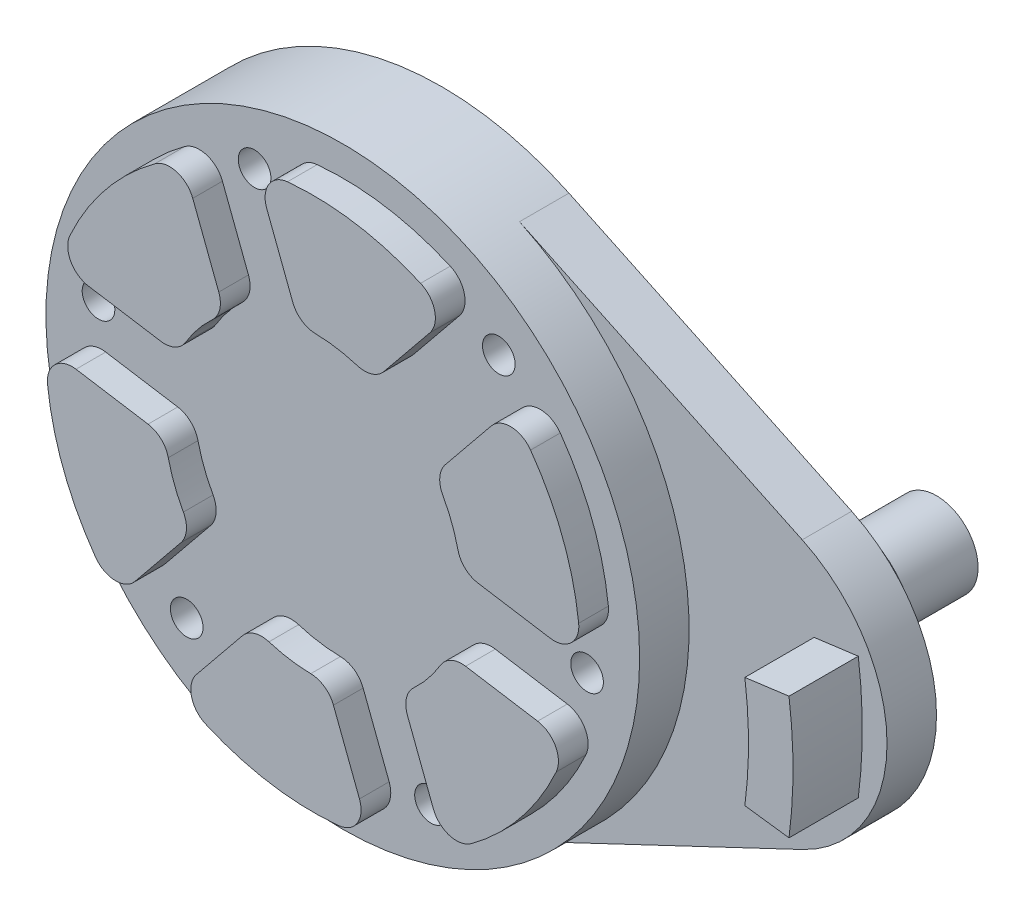
SolidWorks part; units mm, degrees
ref_plane "前视基准面" through (0, 0, 0) normal (0, 0, 1) x (1, 0, 0)
ref_plane "上视基准面" through (0, 0, 0) normal (0, 1, 0) x (1, 0, 0)
ref_plane "右视基准面" through (0, 0, 0) normal (1, 0, 0) x (0, 0, -1)
other "Configuration Table"
sketch "草图1" plane through (0, 0, 0) normal (0, 0, 1) x (1, 0, 0)
  line L0 (12.8571, 27.1052) -> (41.4286, 13.5526)
  line L1 (0, 0) -> (35, 0) construction
  line L2 (12.8571, -27.1052) -> (41.4286, -13.5526)
  arc A0 (12.8571, 27.1052) -> (12.8571, -27.1052) centre (0, 0) ccw
  arc A1 (41.4286, -13.5526) -> (41.4286, 13.5526) centre (35, 0) ccw
  dimension "D1" = 30
  dimension "D2" = 15
  dimension "D3" = 35
extrude "凸台-拉伸1" add sketch "草图1" along normal blind 10
sketch "草图2" plane through (0, 0, 10) normal (0, 0, 1) x (1, 0, 0)
  line L0 (23.9574, 0.2099) -> (16.6764, 1.3773) construction
  line L1 (13.353, 10.0845) -> (18.0045, 15.8063) construction
  line L2 (23.9574, 0.2099) -> (16.6764, 1.3773)
  line L3 (13.353, 10.0845) -> (18.0045, 15.8063)
  line L4 (15.4099, -6.5218) -> (22.6909, -7.6892)
  line L5 (12.1605, -20.6428) -> (9.531, -13.7536)
  line L6 (2.0569, -16.6063) -> (4.6864, -23.4955)
  line L7 (-11.7969, -20.8526) -> (-7.1455, -15.1308)
  line L8 (-13.353, -10.0845) -> (-18.0045, -15.8063)
  line L9 (-23.9574, -0.2099) -> (-16.6764, -1.3773)
  line L10 (-15.4099, 6.5218) -> (-22.6909, 7.6892)
  line L11 (-12.1605, 20.6428) -> (-9.531, 13.7536)
  line L12 (-2.0569, 16.6063) -> (-4.6864, 23.4955)
  line L13 (11.7969, 20.8526) -> (7.1455, 15.1308)
  arc A0 (21.9795, 15.6812) -> (18.0045, 15.8063) centre (19.9444, 14.2293) ccw construction
  arc A1 (26.8382, 2.9517) -> (21.9795, 15.6812) centre (0, 0) ccw construction
  arc A2 (26.8216, 2.2826) -> (26.8382, 2.9517) centre (24.3532, 2.6784) ccw construction
  arc A3 (23.9574, 0.2099) -> (26.8216, 2.2826) centre (24.3532, 2.6784) ccw construction
  arc A4 (14.6333, 3.2964) -> (16.6764, 1.3773) centre (17.0722, 3.8458) ccw construction
  arc A5 (14.6333, 3.2964) -> (13.1082, 7.2921) centre (0, 0) ccw construction
  arc A6 (12.8244, 8.9033) -> (13.1082, 7.2921) centre (15.2929, 8.5075) ccw construction
  arc A7 (13.353, 10.0845) -> (12.8244, 8.9033) centre (15.2929, 8.5075) ccw construction
  arc A8 (21.9795, 15.6812) -> (18.0045, 15.8063) centre (19.9444, 14.2293) ccw
  arc A9 (26.8382, 2.9517) -> (21.9795, 15.6812) centre (0, 0) ccw
  arc A10 (26.8216, 2.2826) -> (26.8382, 2.9517) centre (24.3532, 2.6784) ccw
  arc A11 (23.9574, 0.2099) -> (26.8216, 2.2826) centre (24.3532, 2.6784) ccw
  arc A12 (14.6333, 3.2964) -> (16.6764, 1.3773) centre (17.0722, 3.8458) ccw
  arc A13 (14.6333, 3.2964) -> (13.1082, 7.2921) centre (0, 0) ccw
  arc A14 (12.8244, 8.9033) -> (13.1082, 7.2921) centre (15.2929, 8.5075) ccw
  arc A15 (13.353, 10.0845) -> (12.8244, 8.9033) centre (15.2929, 8.5075) ccw
  arc A16 (24.5701, -11.1942) -> (22.6909, -7.6892) centre (22.2951, -10.1577) ccw
  arc A17 (15.4099, -6.5218) -> (14.1227, -6.6547) centre (15.0141, -8.9903) ccw
  arc A18 (14.1227, -6.6547) -> (12.8693, -7.706) centre (15.0141, -8.9903) ccw
  arc A19 (10.1714, -11.0246) -> (12.8693, -7.706) centre (0, 0) ccw
  arc A20 (10.1714, -11.0246) -> (9.531, -13.7536) centre (11.8666, -12.8621) ccw
  arc A21 (12.1605, -20.6428) -> (15.3876, -22.0869) centre (14.4961, -19.7513) ccw
  arc A22 (15.3876, -22.0869) -> (15.9753, -21.7667) centre (14.4961, -19.7513) ccw
  arc A23 (15.9753, -21.7667) -> (24.5701, -11.1942) centre (0, 0) ccw
  arc A24 (2.5906, -26.8754) -> (4.6864, -23.4955) centre (2.3507, -24.387) ccw
  arc A25 (2.0569, -16.6063) -> (1.2982, -15.5579) centre (-0.2788, -17.4978) ccw
  arc A26 (1.2982, -15.5579) -> (-0.2389, -14.9981) centre (-0.2788, -17.4978) ccw
  arc A27 (-4.4619, -14.321) -> (-0.2389, -14.9981) centre (0, 0) ccw
  arc A28 (-4.4619, -14.321) -> (-7.1455, -15.1308) centre (-5.2056, -16.7078) ccw
  arc A29 (-11.7969, -20.8526) -> (-11.434, -24.3695) centre (-9.8571, -22.4296) ccw
  arc A30 (-11.434, -24.3695) -> (-10.8629, -24.7184) centre (-9.8571, -22.4296) ccw
  arc A31 (-10.8629, -24.7184) -> (2.5906, -26.8754) centre (0, 0) ccw
  arc A32 (-21.9795, -15.6812) -> (-18.0045, -15.8063) centre (-19.9444, -14.2293) ccw
  arc A33 (-13.353, -10.0845) -> (-12.8244, -8.9033) centre (-15.2929, -8.5075) ccw
  arc A34 (-12.8244, -8.9033) -> (-13.1082, -7.2921) centre (-15.2929, -8.5075) ccw
  arc A35 (-14.6333, -3.2964) -> (-13.1082, -7.2921) centre (0, 0) ccw
  arc A36 (-14.6333, -3.2964) -> (-16.6764, -1.3773) centre (-17.0722, -3.8458) ccw
  arc A37 (-23.9574, -0.2099) -> (-26.8216, -2.2826) centre (-24.3532, -2.6784) ccw
  arc A38 (-26.8216, -2.2826) -> (-26.8382, -2.9517) centre (-24.3532, -2.6784) ccw
  arc A39 (-26.8382, -2.9517) -> (-21.9795, -15.6812) centre (0, 0) ccw
  arc A40 (-24.5701, 11.1942) -> (-22.6909, 7.6892) centre (-22.2951, 10.1577) ccw
  arc A41 (-15.4099, 6.5218) -> (-14.1227, 6.6547) centre (-15.0141, 8.9903) ccw
  arc A42 (-14.1227, 6.6547) -> (-12.8693, 7.706) centre (-15.0141, 8.9903) ccw
  arc A43 (-10.1714, 11.0246) -> (-12.8693, 7.706) centre (0, 0) ccw
  arc A44 (-10.1714, 11.0246) -> (-9.531, 13.7536) centre (-11.8666, 12.8621) ccw
  arc A45 (-12.1605, 20.6428) -> (-15.3876, 22.0869) centre (-14.4961, 19.7513) ccw
  arc A46 (-15.3876, 22.0869) -> (-15.9753, 21.7667) centre (-14.4961, 19.7513) ccw
  arc A47 (-15.9753, 21.7667) -> (-24.5701, 11.1942) centre (0, 0) ccw
  arc A48 (-2.5906, 26.8754) -> (-4.6864, 23.4955) centre (-2.3507, 24.387) ccw
  arc A49 (-2.0569, 16.6063) -> (-1.2982, 15.5579) centre (0.2788, 17.4978) ccw
  arc A50 (-1.2982, 15.5579) -> (0.2389, 14.9981) centre (0.2788, 17.4978) ccw
  arc A51 (4.4619, 14.321) -> (0.2389, 14.9981) centre (0, 0) ccw
  arc A52 (4.4619, 14.321) -> (7.1455, 15.1308) centre (5.2056, 16.7078) ccw
  arc A53 (11.7969, 20.8526) -> (11.434, 24.3695) centre (9.8571, 22.4296) ccw
  arc A54 (11.434, 24.3695) -> (10.8629, 24.7184) centre (9.8571, 22.4296) ccw
  arc A55 (10.8629, 24.7184) -> (-2.5906, 26.8754) centre (0, 0) ccw
  point P88 (0, 0)
  dimension "D1" = 6
extrude "凸台-拉伸2" add sketch "草图2" along normal blind 3
ref_plane "基准面1" through (3.6908, -30.7022, 61) normal (0.3566, -0.9343, 0) x (-0.9343, -0.3566, 0)
sketch "草图4" plane through (0, 0, 10) normal (0, 0, 1) x (1, 0, 0)
  arc A0 (26.3139, -4.219) -> (23.0555, -3.6966) centre (24.6847, -3.9578) ccw construction
  arc A1 (23.0555, -3.6966) -> (26.3139, -4.219) centre (24.6847, -3.9578) ccw construction
  arc A2 (26.3139, -4.219) -> (23.0555, -3.6966) centre (24.6847, -3.9578) ccw
  arc A3 (23.0555, -3.6966) -> (26.3139, -4.219) centre (24.6847, -3.9578) ccw
  arc A54 (9.5032, -24.898) -> (8.3264, -21.815) centre (8.9148, -23.3565) ccw
  arc A55 (8.3264, -21.815) -> (9.5032, -24.898) centre (8.9148, -23.3565) ccw
  arc A56 (-16.8108, -20.679) -> (-14.7291, -18.1184) centre (-15.7699, -19.3987) ccw
  arc A57 (-14.7291, -18.1184) -> (-16.8108, -20.679) centre (-15.7699, -19.3987) ccw
  arc A58 (-26.3139, 4.219) -> (-23.0555, 3.6966) centre (-24.6847, 3.9578) ccw
  arc A59 (-23.0555, 3.6966) -> (-26.3139, 4.219) centre (-24.6847, 3.9578) ccw
  arc A60 (-9.5032, 24.898) -> (-8.3264, 21.815) centre (-8.9148, 23.3565) ccw
  arc A61 (-8.3264, 21.815) -> (-9.5032, 24.898) centre (-8.9148, 23.3565) ccw
  arc A62 (16.8108, 20.679) -> (14.7291, 18.1184) centre (15.7699, 19.3987) ccw
  arc A63 (14.7291, 18.1184) -> (16.8108, 20.679) centre (15.7699, 19.3987) ccw
  point P20 (4.6739, -5.4737)
  point P21 (1.8316, -3.4892)
  point P22 (30.2146, 39.6891)
  point P23 (4.6903, -3.9932)
  point P24 (0, 0)
  point P25 (-2.658, 2.5046)
  dimension "D1" = 6
extrude "切除-拉伸1" cut sketch "草图4" against normal through all
sketch "草图5" plane through (0, 0, 10) normal (0, 0, 1) x (1, 0, 0)
  line L0 (41.4286, 13.5526) -> (12.8571, 27.1052)
  line L1 (41.4286, -13.5526) -> (12.8571, -27.1052)
  arc A0 (41.4286, -13.5526) -> (41.4286, 13.5526) centre (35, 0) ccw
  arc A1 (12.8571, -27.1052) -> (12.8571, 27.1052) centre (0, 0) ccw
extrude "切除-拉伸2" cut sketch "草图5" against normal blind 5
sketch "草图6" plane through (0, 0, 0) normal (0, 0, -1) x (-1, 0, 0)
  circle A0 centre (-35, 0) radius 4.2
extrude "凸台-拉伸3" add sketch "草图6" along normal blind 15
sketch "草图7" plane through (0, 0, 0) normal (0, 0, -1) x (-1, 0, 0)
  circle A0 centre (-35, 0) radius 8
extrude "凸台-拉伸4" add sketch "草图7" along normal blind 5
sketch "草图8" plane through (0, 0, 5) normal (0, 0, 1) x (1, 0, 0)
  line L0 (0, 0) -> (47.5, 0) construction
  line L1 (42.6321, 5.6126) -> (47.0936, 6.2)
  line L2 (42.6321, -5.6126) -> (47.0936, -6.2)
  line L3 (42.6321, -5.6126) -> (47.0936, -6.2)
  arc A0 (42.6321, -5.6126) -> (42.6321, 5.6126) centre (0, 0) ccw
  arc A1 (47.0936, -6.2) -> (47.0936, 6.2) centre (0, 0) ccw
  dimension "D1" = 7.5
  dimension "D3" = 43
  dimension "D2" = 7.5
extrude "凸台-拉伸6" add sketch "草图8" along normal blind 7 contours A0 L0 A1 L1 | L0 A0 L2 A1
